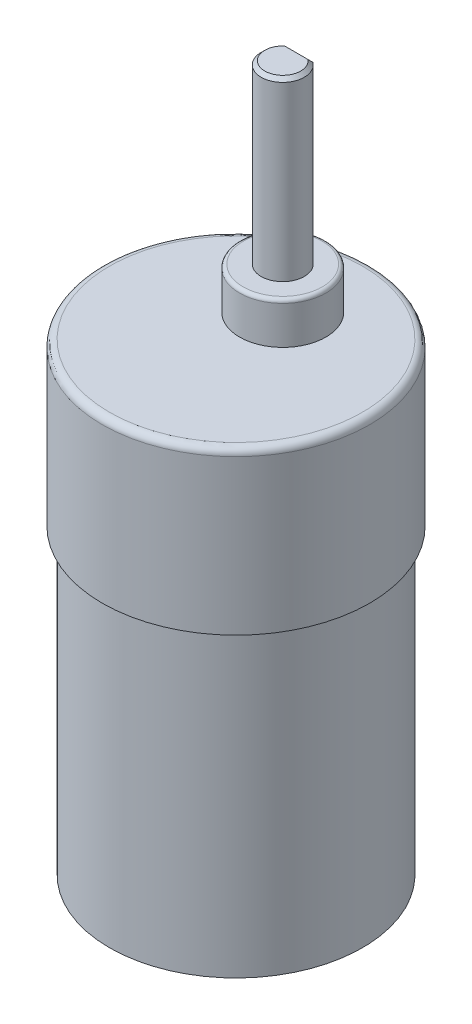
SolidWorks part; units mm, degrees
other "Defeature"
material "Alloy Steel"
ref_plane "Front Plane" through (0, 0, 0) normal (0, 0, 1) x (1, 0, 0)
ref_plane "Top Plane" through (0, 0, 0) normal (0, 1, 0) x (1, 0, 0)
ref_plane "Right Plane" through (0, 0, 0) normal (1, 0, 0) x (0, 0, -1)
sketch "Sketch1" plane through (0, 0, 0) normal (0, 1, 0) x (1, 0, 0)
  circle A0 centre (0, 0) radius 18.6
  dimension "D1" = 37.2
extrude "Boss-Extrude1" add sketch "Sketch1" along normal blind 22.5
sketch "Sketch2" plane through (0, 22.5, 0) normal (0, 1, 0) x (1, 0, 0)
  circle A0 centre (0, 6.5) radius 6
  circle A1 centre (0, 0) radius 18.6 construction
  dimension "D1" = 12
  dimension "D2" = 6.5
extrude "Boss-Extrude2" add sketch "Sketch2" along normal blind 5.8
sketch "Sketch3" plane through (0, 28.3, 0) normal (0, 1, 0) x (1, 0, 0)
  line L0 (-1.8, 8.9) -> (1.8, 8.9)
  arc A0 (-1.8, 8.9) -> (1.8, 8.9) centre (0, 6.5) ccw
  point P1 (0, 3.5)
  dimension "D1" = 6
  dimension "D3" = 5.4
extrude "Boss-Extrude3" add sketch "Sketch3" along normal blind 24.5 separate body
sketch "Sketch4" plane through (0, 0, 0) normal (0, -1, 0) x (1, 0, 0)
  circle A0 centre (0, 0) radius 17.6
  dimension "D1" = 35.2
extrude "Boss-Extrude4" add sketch "Sketch4" along normal blind 42
sketch "Sketch5" plane through (0, -42, 0) normal (0, -1, 0) x (1, 0, 0)
  circle A0 centre (0, 0) radius 17
  dimension "D1" = 34
extrude "Cut-Extrude1" cut sketch "Sketch5" against normal blind 1
sketch "Sketch6" plane through (0, -41, 0) normal (0, -1, 0) x (1, 0, 0)
  circle A0 centre (0, 0) radius 4.9
  dimension "D1" = 9.8
extrude "Boss-Extrude5" add sketch "Sketch6" along normal blind 3.7
sketch "Sketch8" plane through (0, -41, 0) normal (0, -1, 0) x (1, 0, 0)
  line L8 (0, 0) -> (0, -18.6) construction
  line L13 (-7.9436, -7.0053) -> (7.9436, -7.0053) construction
  line L22 (7.9436, -7.0053) -> (8.4094, -6.8235)
  line L23 (9.0344, -9.8) -> (7.9436, -7.0053)
  line L24 (9.5002, -9.6182) -> (9.0344, -9.8)
  line L25 (9.0344, -9.8) -> (8.4094, -6.8235) construction
  line L26 (8.4094, -6.8235) -> (9.5002, -9.6182)
  line L27 (-8.7219, -8.3118) -> (8.7219, -8.3118) construction
  line L28 (-8.4094, -6.8235) -> (-7.9436, -7.0053)
  line L29 (-9.0344, -9.8) -> (-9.5002, -9.6182)
  line L30 (-7.9436, -7.0053) -> (-9.0344, -9.8)
  line L31 (-9.5002, -9.6182) -> (-8.4094, -6.8235)
  line L32 (-9.0344, -9.8) -> (-8.4094, -6.8235) construction
  circle A0 centre (0, 0) radius 18.6 construction
  point P0 (0, -7.0053)
  point P28 (8.7219, -8.3118)
  point P36 (-8.7219, -8.3118)
  dimension "D6" = 3
  dimension "D7" = 8.8
  dimension "D8" = 14.8
  dimension "D9" = 0.5
  dimension "D10" = 17.7
extrude "Boss-Extrude7" add sketch "Sketch8" along normal blind 5
sketch "Sketch9" plane through (-5.3594, 0, -0.3841) normal (0.9316, 0, -0.3636) x (-0.3636, 0, -0.9316)
  line L1 (10.1076, -46) -> (7.1076, -46) construction
  circle A0 centre (8.6076, -45) radius 0.5
  point P6 (8.6076, -46)
  dimension "D1" = 1
  dimension "D2" = 1
extrude "Cut-Extrude3" cut sketch "Sketch9" against normal through all
sketch "Sketch10" plane through (4.134, 0, 2.7557) normal (0.9316, 0, 0.3636) x (0.3636, 0, -0.9316)
  line L1 (10.4781, -46) -> (13.4781, -46) construction
  circle A0 centre (11.9781, -45) radius 0.5
  point P6 (11.9781, -46)
  dimension "D1" = 1
  dimension "D2" = 1
extrude "Cut-Extrude4" cut sketch "Sketch10" along normal through all
chamfer "Chamfer2" distance 0.5 angle 45 2 edges at (8.1765, -46, -6.9144) (9.2673, -46, -9.7091)
chamfer "Chamfer3" distance 0.5 angle 45 2 edges at (-8.1765, -46, -6.9144) (-9.2673, -46, -9.7091)
fillet "Fillet2" radius 1 1 edges at (0, 22.5, 18.6)
fillet "Fillet3" radius 0.5 1 edges at (0, 28.3, -0.5)
chamfer "Chamfer4" distance 0.5 angle 45 2 edges at (0, 52.8, -8.9) (0, 52.8, -3.5)
fillet "Fillet4" radius 2 1 edges at (0, -44.7, -4.9)
